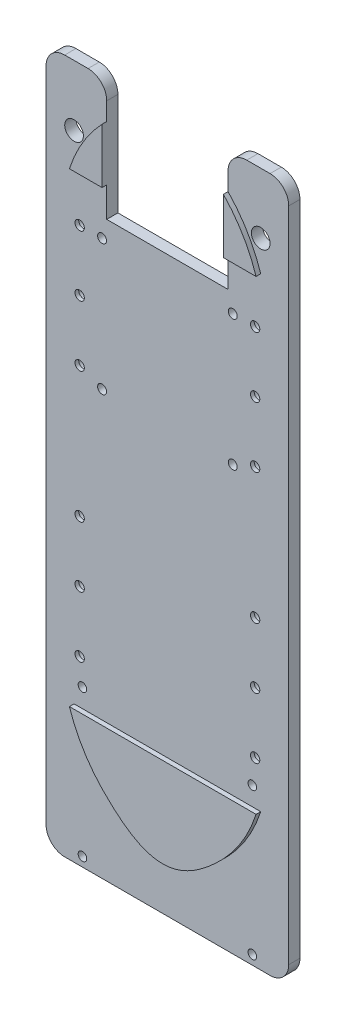
SolidWorks part; units mm, degrees
ref_plane "前视基准面" through (0, 0, 0) normal (0, 0, 1) x (1, 0, 0)
ref_plane "上视基准面" through (0, 0, 0) normal (0, 1, 0) x (1, 0, 0)
ref_plane "右视基准面" through (0, 0, 0) normal (1, 0, 0) x (0, 0, -1)
ref_plane "基准面4" through (0, 0, 0) normal (0, 0, -1) x (-1, 0, 0)
sketch "草图1" plane through (0, 0, 0) normal (0, 0, -1) x (-1, 0, 0)
  line L0 (0, 0) -> (-130, 0)
  line L1 (-130, 0) -> (-130, -347)
  line L2 (-130, -347) -> (0, -347)
  line L3 (0, -347) -> (0, 0)
extrude "凸台-拉伸1" add sketch "草图1" against normal blind 6
sketch "草图2" plane through (0, 0, 6) normal (0, 0, 1) x (1, 0, 0)
  line L0 (15, -298.5) -> (115, -298.5)
  arc A0 (32.5, -327.8968) -> (15, -298.5) centre (88.1109, -274.8841) cw
  arc A1 (115, -298.5) -> (97.5, -327.8968) centre (42.2407, -275.0934) cw
  spline S0 degree 3 poles (32.5, -327.8968) (55.7969, -351.8857) (72.6799, -353.4541) (97.5, -327.8968) knots 0 0 0 0 1 1 1 1
extrude "凸台-拉伸2" add sketch "草图2" along normal blind 2.5
sketch "草图3" plane through (0, 0, 6) normal (0, 0, 1) x (1, 0, 0)
  line L0 (97.5, 0) -> (32.5, 0)
  line L1 (32.5, 0) -> (32.5, -65)
  line L2 (32.5, -65) -> (97.5, -65)
  line L3 (97.5, -65) -> (97.5, 0)
extrude "切除-拉伸1" cut sketch "草图3" against normal through all
sketch "草图4" plane through (0, 0, 6) normal (0, 0, 1) x (1, 0, 0)
  line L0 (115, -49) -> (97.5, -49)
  line L1 (97.5, -49) -> (97.5, -19.6032)
  arc A0 (115, -49) -> (97.5, -19.6032) centre (42.2407, -72.4066) ccw
extrude "凸台-拉伸3" add sketch "草图4" along normal blind 2.5
sketch "草图5" plane through (0, 0, 6) normal (0, 0, 1) x (1, 0, 0)
  line L0 (32.5, -19.6032) -> (32.5, -49)
  line L1 (32.5, -49) -> (15, -49)
  arc A0 (32.5, -19.6032) -> (15, -49) centre (88.1109, -72.6159) ccw
extrude "凸台-拉伸4" add sketch "草图5" along normal blind 2.5
hole_wizard "Ø10.0 (10) 直径孔1" positions "草图7" profile "草图6" hole size "Ø10.0" standard "ANSI Metric"
sketch "草图7" plane through (0, 0, 6) normal (0, 0, 1) x (1, 0, 0)
  point P0 (15, -32.5)
  point P1 (115, -32.5)
sketch "草图6" plane through (15, -32.5, 6) normal (1, 0, 0) x (0, -1, 0)
  line L0 (0, 0) -> (0, 6)
  line L1 (0, 6) -> (5, 6)
  line L2 (5, 6) -> (5, 0)
  line L5 (5, 0) -> (0, 0)
  line L11 (0, -6.35) -> (0, 107.95) construction
  dimension "通孔孔直径" = 10
  dimension "通孔孔深度" = 6
hole_wizard "Ø4.8 (4.8) 直径孔1" positions "草图9" profile "草图8" hole size "Ø4.8" standard "ANSI Metric" end condition through all
sketch "草图9" plane through (0, 0, 6) normal (0, 0, 1) x (1, 0, 0)
  point P0 (100, -75)
  point P1 (30, -145)
  point P2 (100, -145)
  point P3 (30, -75)
sketch "草图8" plane through (100, -75, 6) normal (1, 0, 0) x (0, -1, 0)
  line L0 (0, 0) -> (0, 6)
  line L1 (0, 6) -> (2.4, 6)
  line L2 (2.4, 6) -> (2.4, 0)
  line L5 (2.4, 0) -> (0, 0)
  line L11 (0, -6.35) -> (0, 107.95) construction
  dimension "通孔孔直径" = 4.8
  dimension "通孔孔深度" = 6
hole_wizard "孔1" positions "草图13" profile "草图12" legacy
sketch "草图13" plane through (0, 0, 0) normal (0, 0, -1) x (-1, 0, 0)
  point P0 (-18, -75)
  point P1 (-112, -210)
  point P2 (-112, -140)
  point P3 (-112, -107.5)
  point P4 (-18, -107.5)
  point P5 (-18, -140)
  point P6 (-18, -210)
  point P7 (-18, -242.5)
  point P8 (-18, -275)
  point P9 (-112, -275)
  point P10 (-112, -242.5)
  point P11 (-112, -75)
  dimension "D1" = 94
  dimension "D2" = 32.5
  dimension "D3" = 32.5
  dimension "D4" = 70
  dimension "D5" = 32.5
  dimension "D6" = 32.5
sketch "草图12" plane through (18, -75, 0) normal (1, 0, 0) x (0, 1, 0)
  line L0 (0, 0) -> (0, 8.5)
  line L1 (0, 8.5) -> (2.5, 8.5)
  line L2 (2.5, 8.5) -> (2.5, 4)
  line L3 (2.5, 4) -> (3.6, 4)
  line L4 (3.6, 4) -> (3.6, 0)
  line L5 (3.6, 0) -> (0, 0)
  line L6 (0, 110) -> (0, -10) construction
  dimension "直径" = 5
  dimension "深度" = 8.5
  dimension "柱坑直径" = 7.2
  dimension "柱坑深度" = 4
fillet "圆角1" radius 10 4 edges at (32.5, 0, 3) (97.5, 0, 3) (0, 0, 3) (130, 0, 3)
sketch "草图14" plane through (0, -347, 0) normal (0, -1, 0) x (1, 0, 0)
  line L4 (0, 0) -> (130, 0)
  line L5 (130, 0) -> (130, 6)
  line L6 (130, 6) -> (0, 6)
  line L7 (0, 6) -> (0, 0)
  line L8 (0, 0) -> (130, 0)
  line L9 (130, 0) -> (130, 6)
  line L10 (130, 6) -> (0, 6)
  line L11 (0, 6) -> (0, 0)
  dimension "D1" = 0
extrude "凸台-拉伸5" add sketch "草图14" along normal blind 25
hole_wizard "M2.5 六角头机械螺钉的柱形沉头孔1" positions "草图11" profile "草图10" counterbore size "M2.5" standard "ANSI Metric"
sketch "草图11" plane through (0, 0, 6) normal (0, 0, 1) x (1, 0, 0)
  line L0 (0, -372) -> (0, -10) construction
  line L2 (130, -372) -> (0, -372) construction
  point P0 (110.5, -288.5)
  point P1 (19.5, -288.5)
  point P2 (19.5, -367)
  point P3 (110.5, -367)
  dimension "D1" = 91
  dimension "D2" = 78.5
  dimension "D3" = 19.5
  dimension "D4" = 5
sketch "草图10" plane through (110.5, -288.5, 6) normal (1, 0, 0) x (0, -1, 0)
  line L0 (0, 0) -> (0, 6)
  line L1 (0, 6) -> (1.5, 6)
  line L3 (1.5, 6) -> (1.5, 3.5)
  line L4 (1.5, 3.5) -> (2.3, 3.5)
  line L5 (2.3, 3.5) -> (2.3, 0)
  line L7 (2.3, 0) -> (0, 0)
  line L11 (0, -6.35) -> (0, 107.95) construction
  dimension "通孔孔直径" = 3
  dimension "通孔孔深度" = 6
  dimension "柱形沉头孔直径" = 4.6
  dimension "柱形沉头孔深度" = 3.5
fillet "圆角2" radius 10 2 edges at (130, -372, 3) (0, -372, 3)
